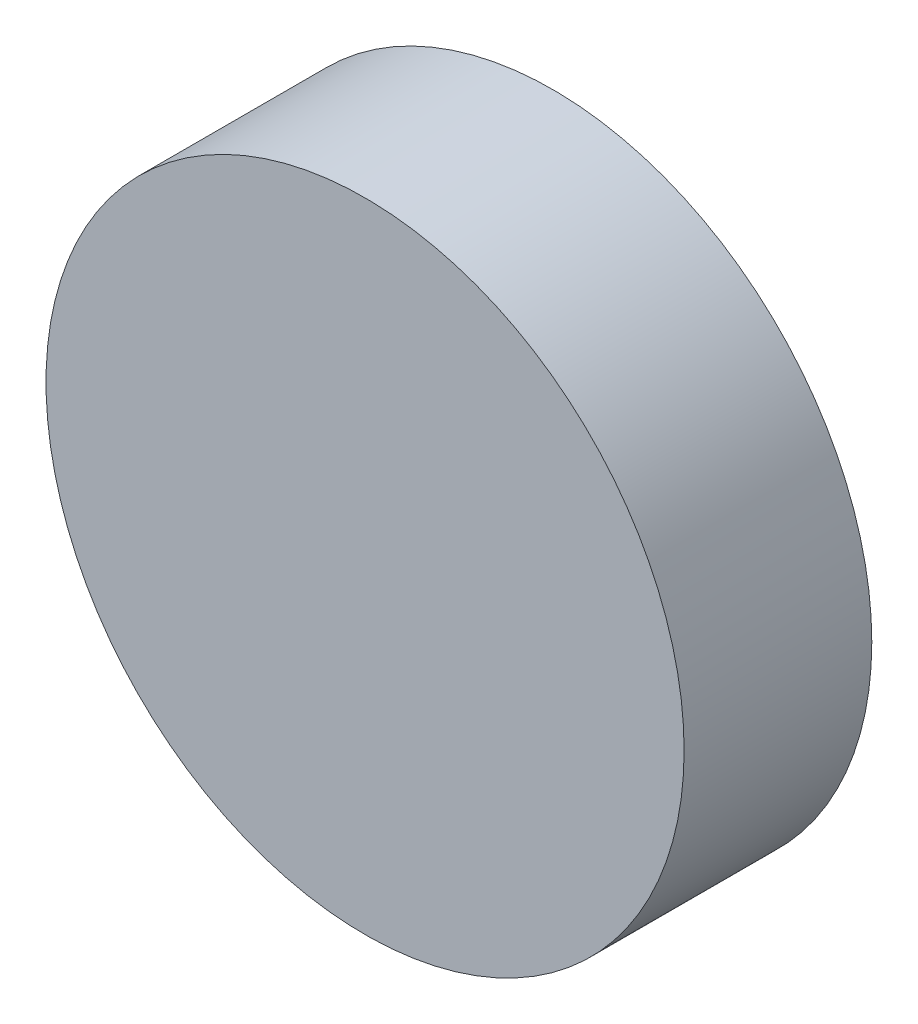
SolidWorks part; units mm, degrees
ref_plane "Płaszczyzna przednia" through (0, 0, 0) normal (0, 0, 1) x (1, 0, 0)
ref_plane "Płaszczyzna górna" through (0, 0, 0) normal (0, 1, 0) x (1, 0, 0)
ref_plane "Płaszczyzna prawa" through (0, 0, 0) normal (1, 0, 0) x (0, 0, -1)
sketch "Szkic1" plane through (0, 0, 0) normal (0, 0, 1) x (1, 0, 0)
  circle A0 centre (0, 0) radius 17
  dimension "D1" = 34
extrude "Dodanie-wyciągnięcie1" add sketch "Szkic1" along normal blind 10
